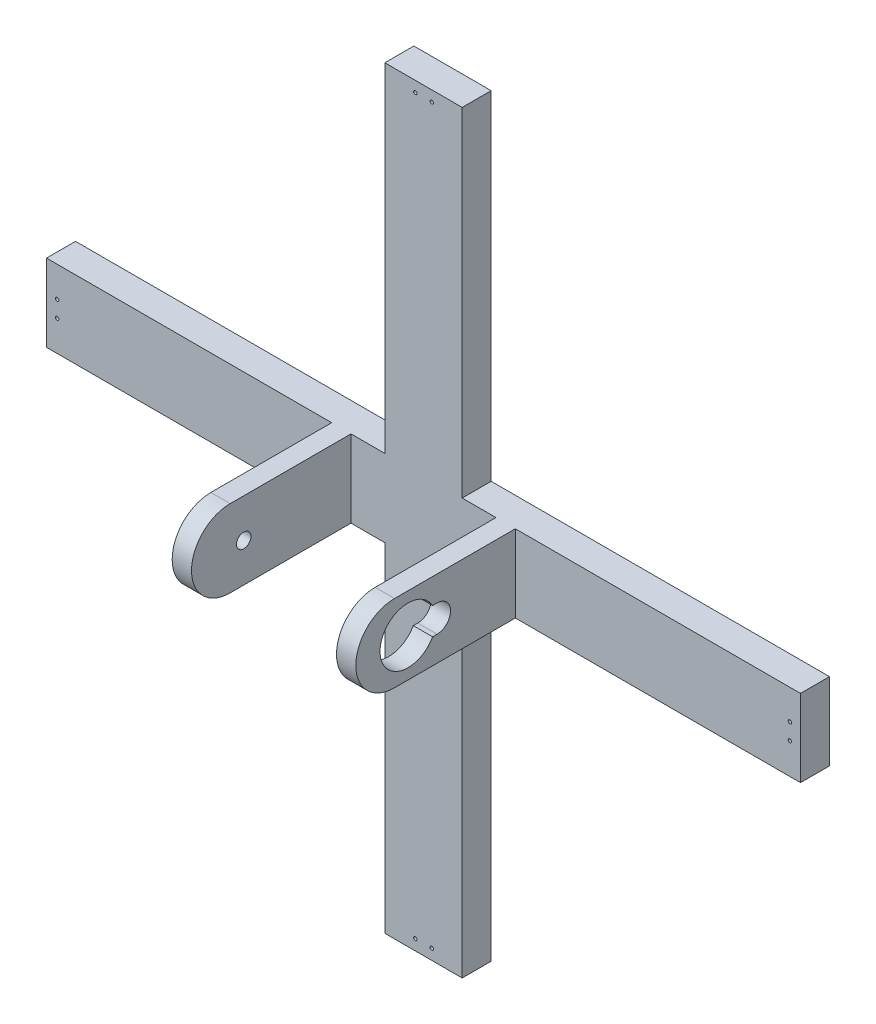
SolidWorks part; units mm, degrees
ref_plane "Ön Düzlem" through (0, 0, 0) normal (0, 0, 1) x (1, 0, 0)
ref_plane "Üst Düzlem" through (0, 0, 0) normal (0, 1, 0) x (1, 0, 0)
ref_plane "Sağ Düzlem" through (0, 0, 0) normal (1, 0, 0) x (0, 0, -1)
sketch "Çizim1" plane through (0, 0, 0) normal (0, 0, 1) x (1, 0, 0)
  line L0 (0, 76.6189) -> (0, 70) construction
  line L1 (8, 70) -> (-8, 70)
  line L2 (-8, 70) -> (-8, 0)
  line L3 (-8, 0) -> (-78, 0)
  line L4 (-78, 0) -> (-78, -16)
  line L5 (-78, -16) -> (-8, -16)
  line L6 (-8, -16) -> (-8, -86)
  line L7 (-8, -86) -> (8, -86)
  line L9 (8, -16) -> (8, -86)
  line L10 (78, -16) -> (8, -16)
  line L11 (78, 0) -> (78, -16)
  line L12 (8, 0) -> (78, 0)
  line L13 (8, 70) -> (8, 0)
  line L14 (0, -86) -> (0, -134.6952) construction
  dimension "D1" = 8
  dimension "D2" = 70
  dimension "D3" = 70
  dimension "D4" = 16
  dimension "D5" = 70
  dimension "D6" = 70
extrude "Yükseklik-Ekstrüzyon1" add sketch "Çizim1" along normal mid plane 6
sketch "Çizim2" plane through (0, 0, 0) normal (0, 0, 1) x (1, 0, 0)
  line L0 (0, 70) -> (0, 67.8) construction
  line L1 (8, 70) -> (-8, 70) construction
  line L2 (0, 67.8) -> (-1.7, 67.8) construction
  line L3 (0, 67.8) -> (1.7, 67.8) construction
  line L4 (0, -86) -> (0, -83.8) construction
  line L5 (-8, -86) -> (8, -86) construction
  line L6 (0, -83.8) -> (-1.7, -83.8) construction
  line L7 (0, -83.8) -> (1.7, -83.8) construction
  circle A0 centre (-75.8, -6.3) radius 0.35
  circle A1 centre (-75.8, -9.7) radius 0.35
  circle A2 centre (-1.7, 67.8) radius 0.35
  circle A3 centre (1.7, 67.8) radius 0.35
  circle A4 centre (75.8049, -6.1988) radius 0.35
  circle A5 centre (75.8049, -9.5988) radius 0.35
  circle A8 centre (-75.8049, 141.7988) radius 0.35
  circle A9 centre (-75.8049, 145.1988) radius 0.35
  circle A10 centre (73.9988, 143.6049) radius 0.35
  circle A11 centre (77.3988, 143.6049) radius 0.35
  circle A12 centre (-73.9988, -8.0049) radius 0.35 [skipped]
  circle A13 centre (-77.3988, -8.0049) radius 0.35 [skipped]
  circle A14 centre (-1.7, -83.8) radius 0.35
  circle A15 centre (1.7, -83.8) radius 0.35
  point P34 (0, 67.8)
  dimension "D4" = 1.7
  dimension "D5" = 1.7
  dimension "D6" = 0.7
  dimension "D7" = 0.7
  dimension "D11" = 0.7
  dimension "D12" = 0.7
  dimension "D1" = 2
  dimension "D2" = 2.2
  dimension "D3" = 4
  dimension "D8" = 1.7
  dimension "D9" = 1.7
  dimension "D10" = 2.2
extrude "Kes-Ekstrüzyon1" cut sketch "Çizim2" against normal mid plane 10
sketch "Çizim3" plane through (0, 0, 0) normal (0, 0, 1) x (1, 0, 0)
  line L0 (0, 61.0899) -> (0, -75.2429) construction
  line L3 (-15, -2.3529) -> (-15, -13.5692) construction
  line L4 (78, 0) -> (8, 0) construction
  line L5 (-8, 0) -> (-78, 0) construction
  line L6 (-15, 0) -> (-19, 0)
  line L7 (-15, 0) -> (-15, -16)
  line L8 (-15, -16) -> (-19, -16)
  line L9 (-19, 0) -> (-19, -16)
  line L10 (-78, -16) -> (-8, -16) construction
  line L11 (15, 0) -> (19, 0)
  line L12 (15, 0) -> (15, -16)
  line L13 (15, -16) -> (19, -16)
  line L14 (19, 0) -> (19, -16)
  line L15 (8, -16) -> (78, -16) construction
extrude "Yükseklik-Ekstrüzyon4" add sketch "Çizim3" along normal blind 36
sketch "Çizim6" plane through (0, 0, 0) normal (1, 0, 0) x (0, 0, -1)
  line L0 (-36, 0) -> (-39.9775, 0)
  line L1 (-39.9775, 0) -> (-39.9775, -16)
  line L2 (-28, 0) -> (-36, 0)
  line L4 (-36, -16) -> (-28, -16)
  line L5 (-39.9775, -16) -> (-36, -16)
  arc A0 (-28, 0) -> (-28, -16) centre (-28, -8) ccw
  dimension "D1" = 8
extrude "Kes-Ekstrüzyon2" cut sketch "Çizim6" against normal through all both and the other way through all
sketch "Çizim7" plane through (0, 0, 0) normal (1, 0, 0) x (0, 0, -1)
  line L3 (-19.4, -8) -> (-19.2, -8) construction
  line L5 (-19.2, -5.2) -> (-20.1206, -5.2)
  line L6 (-19.2, -10.8) -> (-20.1206, -10.8)
  line L7 (-19.4, -8) -> (-19.2, -8) construction
  arc A0 (-19.2, -10.8) -> (-19.2, -5.2) centre (-19.2, -8) ccw
  arc A2 (-20.1206, -5.2) -> (-20.1206, -10.8) centre (-25.2, -8) ccw
extrude "Kes-Ekstrüzyon3" cut sketch "Çizim7" along normal blind 100
ref_plane "Düzlem1" through (-9.5, 0, 0) normal (1, 0, 0) x (0, 0, -1)
sketch "Çizim8" plane through (-9.5, 0, 0) normal (1, 0, 0) x (0, 0, -1)
  line L0 (-36, -8) -> (-25.2, -8) construction
  arc A0 (-28, 0) -> (-28, -16) centre (-28, -8) ccw construction
  circle A1 centre (-25.2, -8) radius 1.5
  dimension "D2" = 3
  dimension "D1" = 10.8
extrude "Kes-Ekstrüzyon4" cut sketch "Çizim8" against normal blind 30
